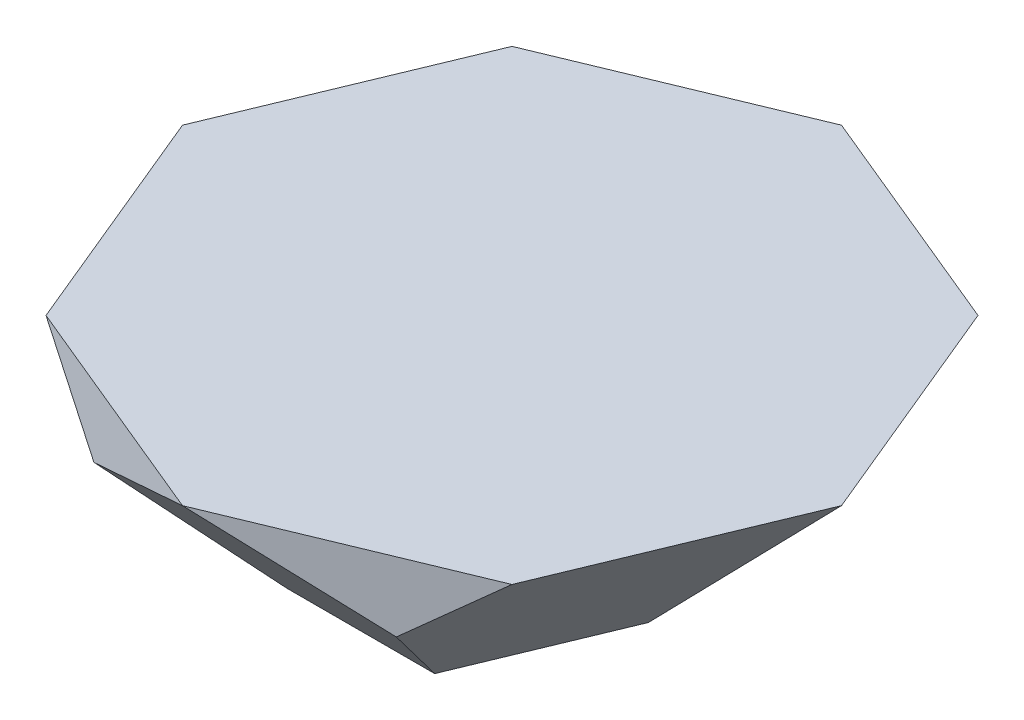
SolidWorks part; units mm, degrees
ref_plane "Ebene vorne" through (0, 0, 0) normal (0, 0, 1) x (1, 0, 0)
ref_plane "Ebene oben" through (0, 0, 0) normal (0, 1, 0) x (1, 0, 0)
ref_plane "Ebene rechts" through (0, 0, 0) normal (1, 0, 0) x (0, 0, -1)
sketch "Skizze1" plane through (0, 0, 0) normal (0, 1, 0) x (1, 0, 0)
  line L1 (-55, 0) -> (55, 0) construction
  line L5 (35.3553, -35.3553) -> (50, 0)
  line L6 (-50, 0) -> (50, 0) construction
  line L7 (0, -55) -> (0, 55) construction
  line L8 (0, 50) -> (0, -50) construction
  line L9 (0, -50) -> (35.3553, -35.3553)
  line L10 (35.3553, 35.3553) -> (-35.3553, -35.3553) construction
  line L11 (35.3553, -35.3553) -> (-35.3553, 35.3553) construction
  line L12 (-35.3553, -35.3553) -> (0, -50)
  line L15 (-50, 0) -> (-35.3553, -35.3553)
  line L16 (-35.3553, 35.3553) -> (-50, 0)
  line L19 (0, 50) -> (-35.3553, 35.3553)
  line L20 (35.3553, 35.3553) -> (0, 50)
  line L23 (50, 0) -> (35.3553, 35.3553)
  point P21 (0, 0)
  dimension "D1" = 45
  dimension "D2" = 100
  dimension "D5" = 4
extrude "Aufsatz-Linear austragen1" add sketch "Skizze1" along normal blind 30
ref_plane "Ebene1" through (21.5045, 0, 51.9165) normal (0.3827, 0, 0.9239) x (0.9239, 0, -0.3827)
sketch "Skizze2" plane through (21.5045, 0, 51.9165) normal (0.3827, 0, 0.9239) x (0.9239, 0, -0.3827)
  line L0 (-46.194, 30) -> (-19.1342, 0)
  line L1 (-46.194, 30) -> (-46.194, 0)
  line L2 (55, 0) -> (-55, 0) construction
  line L3 (-46.194, 30) -> (-46.194, 0) construction
  line L4 (-46.194, 0) -> (-19.1342, 0)
  line L5 (46.194, 30) -> (46.194, 0)
  line L6 (46.194, 30) -> (46.194, 0) construction
  line L7 (46.194, 0) -> (19.1342, 0)
  line L8 (19.1342, 30) -> (19.1342, 0) construction
  line L9 (19.1342, 0) -> (46.194, 30)
extrude "Schnitt-Linear austragen1" cut sketch "Skizze2" against normal through all
ref_plane "Ebene2" through (-21.5045, 0, 51.9165) normal (-0.3827, 0, 0.9239) x (0.9239, 0, 0.3827)
sketch "Skizze3" plane through (-21.5045, 0, 51.9165) normal (-0.3827, 0, 0.9239) x (0.9239, 0, 0.3827)
  line L0 (19.1342, 0) -> (46.194, 30)
  line L1 (46.194, 30) -> (46.194, 0)
  line L2 (55, 0) -> (-55, 0) construction
  line L3 (46.194, 30) -> (46.194, 0) construction
  line L4 (46.194, 0) -> (19.1342, 0)
  line L5 (-46.194, 30) -> (-46.194, 0)
  line L6 (-46.194, 0) -> (-46.194, 30) construction
  line L7 (-46.194, 0) -> (-19.134, 0)
  line L8 (-19.134, 0) -> (-46.194, 30)
  dimension "D1" = 27.06
extrude "Schnitt-Linear austragen2" cut sketch "Skizze3" against normal through all
sketch "Skizze4" plane through (0, 0, 0) normal (1, 0, 0) x (0, 0, -1)
  line L0 (-50, 30) -> (-50, 0)
  line L1 (-50, 0) -> (-22.94, 0)
  line L2 (0, 0) -> (-50, 0) construction
  line L3 (-22.94, 0) -> (-50, 30)
  line L4 (22.9397, 0) -> (49.9997, 0)
  line L5 (49.9997, 0) -> (0, 0) construction
  line L6 (49.9997, 0) -> (50, 30)
  line L7 (50, 30) -> (22.9397, 0)
  dimension "D1" = 27.06
  dimension "D2" = 27.06
extrude "Schnitt-Linear austragen3" cut sketch "Skizze4" against normal through all and the other way through all
